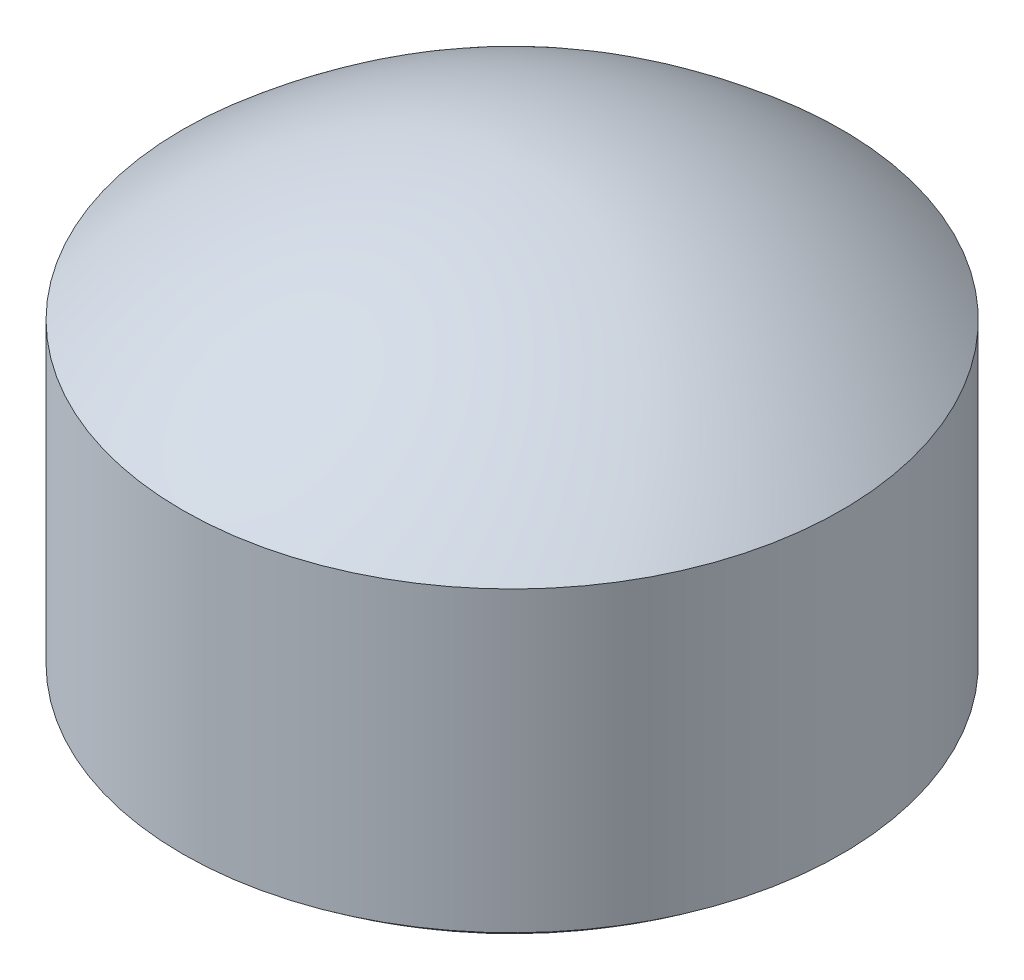
SolidWorks part; units mm, degrees
ref_plane "Front Plane" through (0, 0, 0) normal (0, 0, 1) x (1, 0, 0)
ref_plane "Top Plane" through (0, 0, 0) normal (0, 1, 0) x (1, 0, 0)
ref_plane "Right Plane" through (0, 0, 0) normal (1, 0, 0) x (0, 0, -1)
sketch "Sketch3" plane through (0, 0, 0) normal (0, 0, 1) x (1, 0, 0)
  line L0 (-0.7896, 9.5284) -> (-0.7896, -8.8678) construction
  line L4 (-11.7211, 4.9362) -> (-11.7211, -4.9362)
  line L5 (-0.7896, 9.5284) -> (-0.7896, -8.8678)
  spline S0 degree 2 poles (-0.7896, 9.5284) (-6.4824, 9.4236) (-11.7211, 4.9362) knots 0.514225 0.514225 0.514225 1 1 1
  spline S1 degree 2 poles (-0.7896, -8.8678) (-6.6501, -8.8678) (-11.7211, -4.9362) knots 0.5 0.5 0.5 1 1 1
  point P0 (0, 0)
revolve "Revolve4" add sketch "Sketch3" angle 360 about L0
